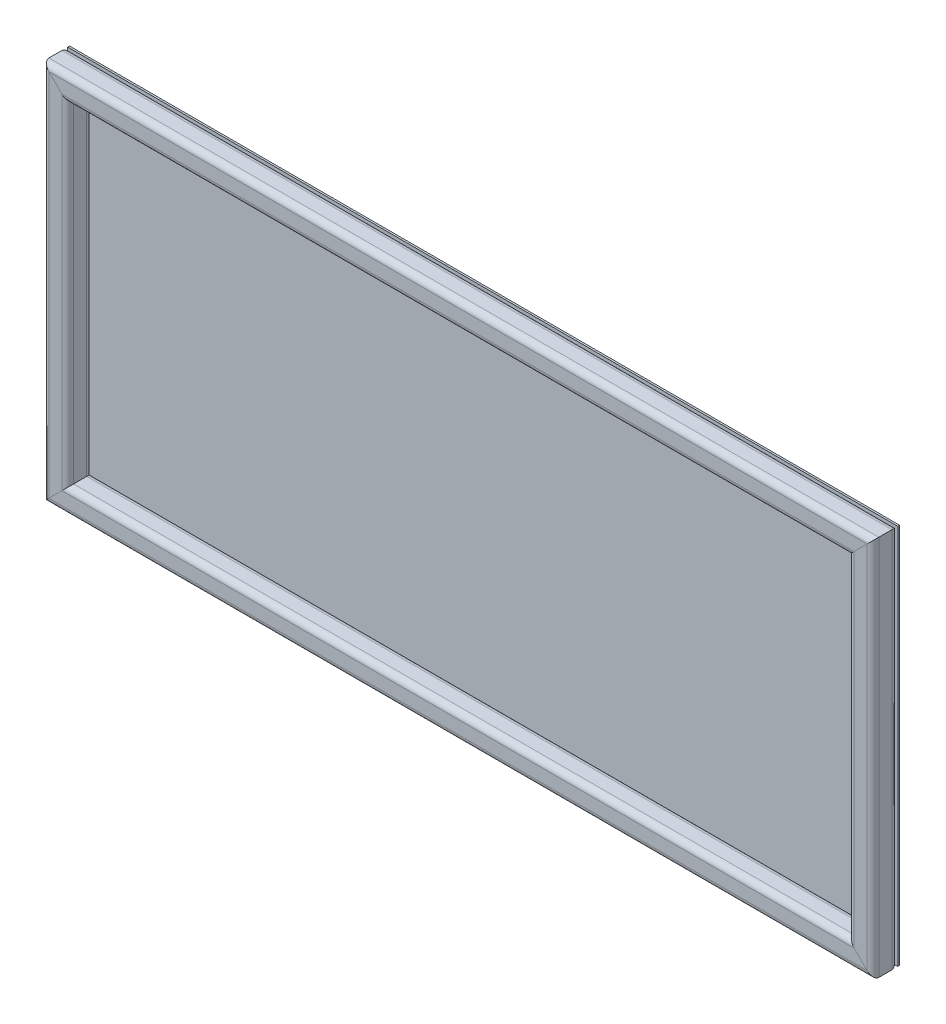
SolidWorks part; units mm, degrees
ref_plane "Alzado" through (0, 0, 0) normal (0, 0, 1) x (1, 0, 0)
ref_plane "Planta" through (0, 0, 0) normal (0, 1, 0) x (1, 0, 0)
ref_plane "Vista lateral" through (0, 0, 0) normal (1, 0, 0) x (0, 0, -1)
sketch "Croquis1" plane through (0, 0, 0) normal (0, 0, 1) x (1, 0, 0)
  line L1 (-400, 170) -> (400, 170)
  line L2 (-400, 170) -> (-400, -170)
  line L3 (-400, -170) -> (400, -170)
  line L4 (400, 170) -> (400, -170)
  line L5 (-400, 170) -> (400, -170) construction
  line L6 (-400, -170) -> (400, 170) construction
  point P0 (0, 0)
  dimension "D1" = 800
  dimension "D2" = 340
other "Tubo cuadrado 2 X 2 X 0.25(1)"
ref_plane "Plano1" through (-412.7, 170, 0) normal (0, -1, 0) x (1, 0, 0)
sketch "Sketch1" plane through (-412.7, 170, 0) normal (0, -1, 0) x (1, 0, 0)
  line L0 (-6.7, -9.7) -> (6.7, -9.7)
  line L1 (-9.7, -6.7) -> (-9.7, 6.7)
  line L2 (6.7, 9.7) -> (-6.7, 9.7)
  line L3 (9.7, 6.7) -> (9.7, -6.7)
  line L4 (-6.7, -12.7) -> (6.7, -12.7)
  line L5 (-12.7, -6.7) -> (-12.7, 6.7)
  line L6 (6.7, 12.7) -> (-6.7, 12.7)
  line L7 (12.7, 6.7) -> (12.7, -6.7)
  line L8 (0, 0) -> (9.7, 0) construction
  line L9 (0, 0) -> (0, 9.7) construction
  arc A0 (12.7, 6.7) -> (6.7, 12.7) centre (6.7, 6.7) ccw
  arc A1 (6.7, -12.7) -> (12.7, -6.7) centre (6.7, -6.7) ccw
  arc A2 (-12.7, -6.7) -> (-6.7, -12.7) centre (-6.7, -6.7) ccw
  arc A3 (-6.7, 12.7) -> (-12.7, 6.7) centre (-6.7, 6.7) ccw
  arc A4 (-6.7, 9.7) -> (-9.7, 6.7) centre (-6.7, 6.7) ccw
  arc A5 (9.7, 6.7) -> (6.7, 9.7) centre (6.7, 6.7) ccw
  arc A6 (6.7, -9.7) -> (9.7, -6.7) centre (6.7, -6.7) ccw
  arc A7 (-9.7, -6.7) -> (-6.7, -9.7) centre (-6.7, -6.7) ccw
  point P3 (0, 12.7)
  point P4 (12.7, 0)
  point P5 (0, -12.7)
  point P6 (-12.7, 0)
  point P7 (-12.7, 12.7)
  point P8 (-12.7, -12.7)
  point P33 (0, 0)
  point P35 (12.7, -12.7)
  point P36 (12.7, 12.7)
  point P37 (0, 0)
  dimension "D1" = 6
  dimension "Thickness" = 3
  dimension "V_leg" = 25.4
sketch "Croquis4" plane through (0, 0, -12.7) normal (0, 0, -1) x (-1, 0, 0)
  line L1 (425.4, -195.4) -> (-425.4, -195.4)
  line L2 (425.4, -195.4) -> (425.4, 195.4)
  line L3 (425.4, 195.4) -> (-425.4, 195.4)
  line L4 (-425.4, -195.4) -> (-425.4, 195.4)
  line L5 (425.4, -195.4) -> (-425.4, 195.4) construction
  line L6 (425.4, 195.4) -> (-425.4, -195.4) construction
  point P0 (0, 0)
extrude "Saliente-Extruir2" add sketch "Croquis4" along normal blind 1.9 separate body
